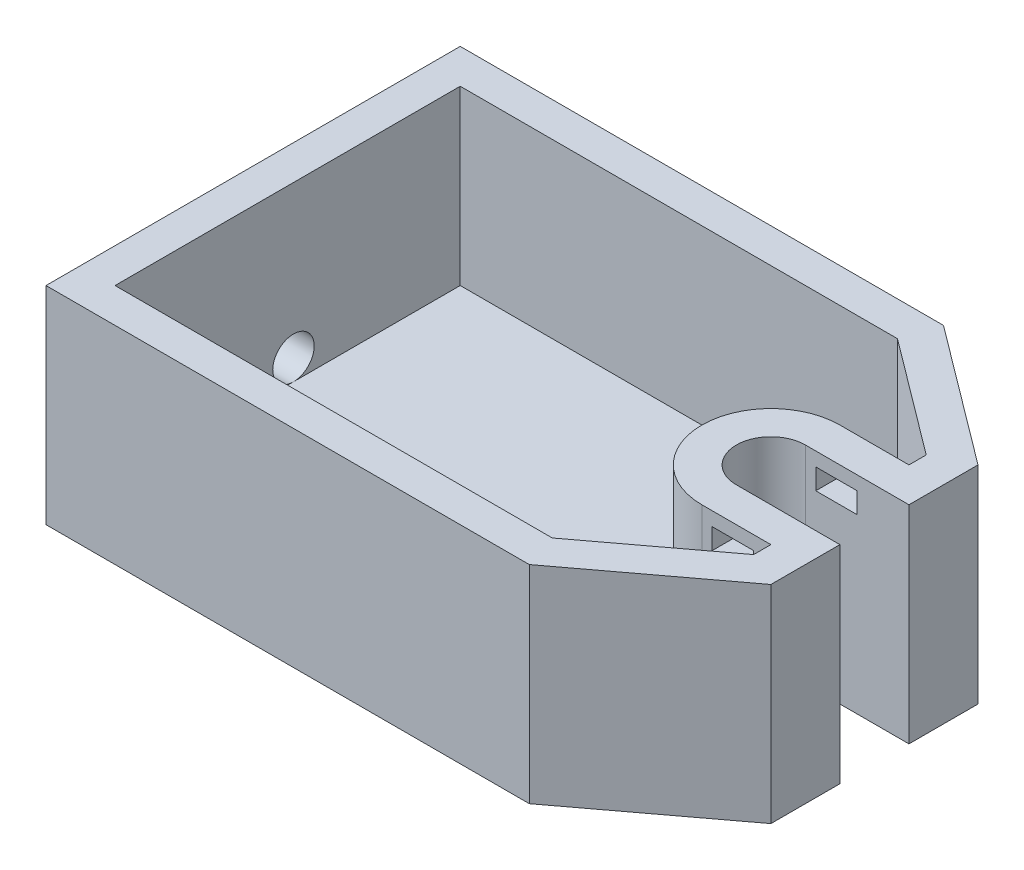
SolidWorks part; units mm, degrees
ref_plane "Front Plane" through (0, 0, 0) normal (0, 0, 1) x (1, 0, 0)
ref_plane "Top Plane" through (0, 0, 0) normal (0, 1, 0) x (1, 0, 0)
ref_plane "Right Plane" through (0, 0, 0) normal (1, 0, 0) x (0, 0, -1)
sketch "Sketch1" plane through (0, 0, 0) normal (0, 1, 0) x (1, 0, 0)
  line L0 (0, 76.2) -> (177.8, 76.2) construction
  line L1 (0, 0) -> (177.8, 0)
  line L2 (0, 0) -> (0, 152.4)
  line L3 (0, 152.4) -> (177.8, 152.4)
  line L4 (177.8, 0) -> (177.8, 152.4)
  line L5 (177.8, 152.4) -> (228.6, 114.3)
  line L6 (177.8, 114.3) -> (228.6, 114.3)
  line L7 (177.8, 114.3) -> (177.8, 38.1)
  line L8 (177.8, 38.1) -> (228.6, 38.1)
  line L9 (228.6, 114.3) -> (228.6, 38.1)
  line L10 (228.6, 38.1) -> (177.8, 0)
  line L12 (177.8, 88.9) -> (228.6, 88.9)
  line L13 (177.8, 88.9) -> (177.8, 63.5)
  line L14 (177.8, 63.5) -> (228.6, 63.5)
  line L15 (228.6, 88.9) -> (228.6, 63.5)
  arc A0 (190.5, 88.9) -> (190.5, 63.5) centre (190.5, 76.2) ccw
  point P14 (228.6, 76.2)
  point P16 (228.6, 76.2)
  point P17 (0, 0)
  dimension "D6" = 12.7
  dimension "D1" = 152.4
  dimension "D2" = 177.8
  dimension "D3" = 50.8
  dimension "D4" = 76.2
  dimension "D5" = 25.4
extrude "Boss-Extrude3" add sketch "Sketch1" along normal blind 76.2 contours L0 L2 L1 L4 L7 | L2 L0 L13 L7 L4 L3 | L4 L6 L5 | L7 L12 L9 L6 | L10 L8 L4 | L14 L4 L8 L9 | A0 L7 L14 | A0 L12 L13
sketch "Sketch4" plane through (0, 76.2, 0) normal (0, 1, 0) x (1, 0, 0)
  line L18 (215.9, 101.6) -> (215.9, 107.95)
  line L19 (215.9, 107.95) -> (173.5667, 139.7)
  line L20 (173.5667, 139.7) -> (12.7, 139.7)
  line L21 (12.7, 139.7) -> (12.7, 12.7)
  line L22 (12.7, 12.7) -> (173.5667, 12.7)
  line L23 (173.5667, 12.7) -> (215.9, 44.45)
  line L24 (215.9, 44.45) -> (215.9, 50.8)
  line L25 (215.9, 50.8) -> (190.5, 50.8)
  line L26 (190.5, 101.6) -> (215.9, 101.6)
  line L27 (215.9, 101.6) -> (215.9, 107.95)
  line L28 (215.9, 107.95) -> (173.5667, 139.7)
  line L29 (173.5667, 139.7) -> (12.7, 139.7)
  line L30 (12.7, 139.7) -> (12.7, 12.7)
  line L31 (12.7, 12.7) -> (173.5667, 12.7)
  line L32 (173.5667, 12.7) -> (215.9, 44.45)
  line L33 (215.9, 44.45) -> (215.9, 50.8)
  line L34 (215.9, 50.8) -> (190.5, 50.8)
  line L35 (190.5, 101.6) -> (215.9, 101.6)
  arc A2 (190.5, 101.6) -> (190.5, 50.8) centre (190.5, 76.2) ccw
  arc A3 (190.5, 101.6) -> (190.5, 50.8) centre (190.5, 76.2) ccw
  dimension "D1" = 12.7
extrude "Cut-Extrude1" cut sketch "Sketch4" against normal offset from surface (63.5 mm away) 12.7 up to face at (163.83, 0, -76.2)
sketch "Sketch6" plane through (0, 0, 0) normal (-1, 0, 0) x (0, 0, 1)
  line L1 (-25.4851, 15.24) -> (-35.6451, 15.24)
  line L2 (-25.4851, 15.24) -> (-25.4851, 25.4)
  line L3 (-25.4851, 25.4) -> (-35.6451, 25.4)
  line L4 (-35.6451, 15.24) -> (-35.6451, 25.4)
  circle A0 centre (-78.3434, 20.32) radius 7.62
  point P7 (0, 0)
  point P8 (-35.6451, 20.32)
  point P9 (0, 0)
  point P11 (0, 0)
  point P12 (0, 0)
  point P13 (0, 0)
  dimension "D4" = 15.24
  dimension "D1" = 10.16
  dimension "D2" = 10.16
  dimension "D3" = 15.24
extrude "Cut-Extrude2" cut sketch "Sketch6" against normal up to surface (12.7 mm away) up to face at (12.7, 44.45, -76.2)
sketch "Sketch12" plane through (0, 0, -50.8) normal (0, 0, 1) x (1, 0, 0)
  line L1 (209.55, 63.5) -> (194.31, 63.5)
  line L2 (209.55, 63.5) -> (209.55, 71.12)
  line L3 (209.55, 71.12) -> (194.31, 71.12)
  line L4 (194.31, 63.5) -> (194.31, 71.12)
  line L5 (215.9, 76.2) -> (190.5, 76.2) construction
  line L6 (215.9, 12.7) -> (215.9, 76.2) construction
  dimension "D1" = 15.24
  dimension "D2" = 7.62
  dimension "D3" = 5.08
  dimension "D4" = 6.35
extrude "Cut-Extrude3" cut sketch "Sketch12" against normal up to surface (50.8 mm away) up to face at (203.2, 44.45, -101.6)
